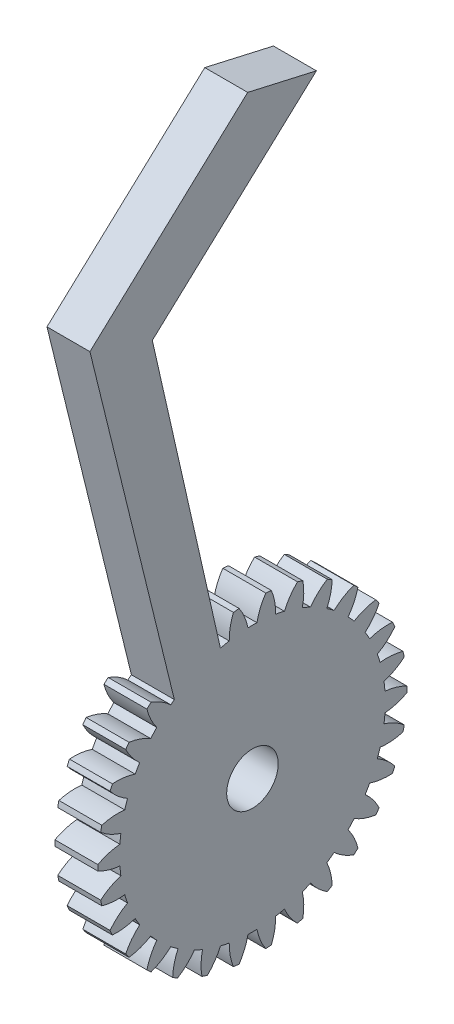
SolidWorks part; units mm, degrees
ref_plane "Plane1" through (0, 0, 0) normal (0, 0, 1) x (1, 0, 0)
ref_plane "Plane2" through (0, 0, 0) normal (0, 1, 0) x (1, 0, 0)
ref_plane "Plane3" through (0, 0, 0) normal (1, 0, 0) x (0, 0, -1)
sketch "HoldingSke" plane through (0, 0, 0) normal (0, 1, 0) x (1, 0, 0)
  line L0 (0, 0) -> (0.7698, -0.4444)
  line L1 (-15, 0) -> (100, 0) construction
  line L2 (0, 0) -> (-2.1039, 2.3779)
  line L3 (0, 0) -> (-11.863, 4.5341)
  line L4 (0, 0) -> (7.479, 4.318)
  line L5 (0, 0) -> (-46.8476, -17.4728)
  line L6 (0, 0) -> (-4.1448, -2.7965)
  line L7 (-2.1039, 2.3779) -> (8.6586, 51.2059)
  line L8 (-76.2, 54.61) -> (-75.2, 54.61)
  line L9 (-71.009, 38.7566) -> (-53.1078, 45.2721)
  line L10 (-76.2, 71.12) -> (104.1128, 71.12)
  line L11 (0, 0) -> (-5, 0)
  line L12 (-76.2, 101.6) -> (-76.158, 101.6)
  line L13 (24.9733, 27.94) -> (52.9518, 28.4284)
  line L14 (24.9733, 27.94) -> (24.9743, 27.94)
  line L15 (24.9733, 27.94) -> (100.4006, 29.5858)
  line L16 (-63.627, -1.125) -> (-12.827, -1.125)
  circle A0 centre (0, 0) radius 3
  circle A1 centre (0, 0) radius 15.4678
  circle A2 centre (0, 0) radius 37.5
  circle A3 centre (0, 0) radius 3
  dimension "MHD" = 30.9355
  dimension "Hub_dia" = 75
  dimension "Bore" = 6
  dimension "MBD" = 6
  dimension "Num_teeth" = 30
  dimension "Pitch_radius" = 180.3128
  dimension "Pitch" = 0.8889
  dimension "Width" = 5
  dimension "Overall_len" = 50
  dimension "Show_teeth" = 30
  dimension "Thickness" = 5
  dimension "OAL" = 50.0001
  dimension "T_dim" = 1
  dimension "Ap" = 20
  dimension "H" = 19.05
  dimension "Backlash" = 0.042
  dimension "Addendum_fac" = 1
  dimension "Dedendum_fac" = 1.25
  dimension "Clearance_fac" = 0.25
  dimension "Dedendum_add" = 0.001
  dimension "Module" = 1.125
sketch "BasProSke" plane through (0, 0, 0) normal (0, 1, 0) x (1, 0, 0)
  line L0 (-10, 0) -> (60, 0) construction
  line L1 (0, 0) -> (0, 18)
  line L2 (0, 0) -> (5, 0)
  line L3 (5, 0) -> (5, 18)
  line L4 (5, 18) -> (0, 18)
  dimension "Diameter" = 36
  dimension "Thickness" = 5
revolve "Base-Revolve" add sketch "BasProSke" angle 360 about L0
sketch "TooCutSke" plane through (0, 0, 0) normal (1, 0, 0) x (0, 0, -1)
  line L1 (0, 0) -> (0, 107) construction
  line L2 (0, 0) -> (-0.9567, 16.8479) construction
  line L3 (0, 0) -> (-3.5238, 33.5265) construction
  line L4 (-0.9567, 16.8479) -> (-1.7619, 16.7632) construction
  arc A0 (0.5235, 15.4589) -> (-0.5235, 15.4589) centre (0, 0) ccw
  arc A1 (1.5687, 17.957) -> (-1.5687, 17.957) centre (0, 0) ccw
  circle A2 centre (0, 0) radius 16.875 construction
  circle A3 centre (0, 0) radius 15.8573 construction
  arc A4 (-0.5235, 15.4589) -> (-1.5687, 17.957) centre (-7.1465, 14.1556) ccw
  arc A5 (1.5687, 17.957) -> (0.5235, 15.4589) centre (7.1465, 14.1556) ccw
  dimension "Root_dia" = 30.9355
  dimension "Overcut_dia" = 36.0508
  dimension "Pitch_dia" = 33.75
  dimension "Base_dia" = 31.7146
  dimension "Flank_rad" = 6.75
  dimension "Half_ang" = 6
  dimension "Half_CT" = 0.8097
extrude "ToothCut" cut sketch "TooCutSke" along normal through all
fillet "Breaks" [suppressed] radius 0.0225
fillet "RootFillets" [suppressed] radius 0.2823
pattern_circular "TeethCuts" count 30 over 360 about axis through (0, 0, 0) along (1, 0, 0) of "ToothCut", "RootFillets", "Breaks"
sketch "HubNeaOneSke" plane through (0, 0, 0) normal (-1, 0, 0) x (0, 0, 1)
  circle A0 centre (0, 0) radius 15.4678
  dimension "Diameter" = 30.9355
extrude "HubNearOne" [suppressed] add sketch "HubNeaOneSke" along normal blind 45.0001
sketch "HubNeaBotSke" plane through (0, 0, 0) normal (-1, 0, 0) x (0, 0, 1)
  circle A0 centre (0, 0) radius 15.4678
  dimension "Diameter" = 30.9355
extrude "HubNearBoth" [suppressed] add sketch "HubNeaBotSke" along normal blind 22.5
ref_plane "FarPln" through (5, 0, 0) normal (1, 0, 0) x (0, 0, -1)
sketch "HubFarSke" plane through (5, 0, 0) normal (1, 0, 0) x (0, 0, -1)
  circle A0 centre (0, 0) radius 15.4678
  dimension "Diameter" = 30.9355
extrude "HubFar" [suppressed] add sketch "HubFarSke" along normal blind 22.5
sketch "BorSke" plane through (0, 0, 0) normal (1, 0, 0) x (0, 0, -1)
  circle A0 centre (0, 0) radius 3
  dimension "Diameter" = 6
extrude "Bore" cut sketch "BorSke" along normal mid plane 100.0001
sketch "KeySke" plane through (0, 0, 0) normal (1, 0, 0) x (0, 0, -1)
  line L0 (-1, 0) -> (-1, 4)
  line L1 (-1, 4) -> (1, 4)
  line L2 (1, 4) -> (1, 0)
  line L3 (0, 0) -> (0, 34) construction
  line L4 (-1, 0) -> (1, 0)
  dimension "Offset" = 4
  dimension "Width" = 2
extrude "Keyway" [suppressed] cut sketch "KeySke" along normal mid plane 100.0001
pattern_circular "Keyway2" [suppressed] count 2 every 90 about axis through (-10, 0, 0) along (1, 0, 0)
sketch "Esquisse2" plane through (5, 0, 0) normal (1, 0, 0) x (0, 0, -1)
  line L0 (-3.7262, 15.0122) -> (-11.6565, 50.0122)
  line L1 (-11.6565, 50.0122) -> (7.45, 67.6457)
  line L2 (7.45, 67.6457) -> (-0.55, 69.4689)
  line L3 (-0.55, 69.4689) -> (-18.9217, 52.5137)
  line L4 (-18.9217, 52.5137) -> (-9.0917, 12.5137)
  line L5 (-3.7262, 15.0122) -> (-9.0917, 12.5137)
  circle A0 centre (23.3529, 39.6852) radius 27.5
  arc A1 (-8.663, 12.8142) -> (-9.51, 12.1988) centre (0, 0) ccw construction
  dimension "D1" = 55
  dimension "D2" = 40
  dimension "D3" = 35
  dimension "D4" = 25
  dimension "D5" = 26
  dimension "D6" = 8
extrude "Boss.-Extru.1" add sketch "Esquisse2" against normal blind 5 contours L2 L3 L4 L5 L0 L1
equation "' \"Module@HoldingSke\" = 6.35"
equation "' \"Num_teeth@HoldingSke\" = 12"
equation "' \"Ap@HoldingSke\" =  20"
equation "' \"Width@HoldingSke\" = 0.5 * 25.4"
equation "' \"Hub_dia@HoldingSke\"= 1 * 25.4"
equation "' \"Overall_len@HoldingSke\" = 1.0 * 25.4"
equation "' \"Bore@HoldingSke\" = 0.75 * 25.4"
equation "' \"T_dim@HoldingSke\" = 0.1 * 25.4"
equation "' \"Width@KeySke\" = 0.25 * 25.4"
equation "' \"Show_teeth@HoldingSke\" = 13"
equation "' \"Backlash@HoldingSke\" = 0.009 * 25.4"
equation "' \"Addendum_fac@HoldingSke\" = 1.0"
equation "' \"Dedendum_fac@HoldingSke\" = 1.25"
equation "' \"Dedendum_add@HoldingSke\" = 0.00005 * 25.4"
equation "' \"Clearance_fac@HoldingSke\" = 0.25"
equation "\"Pitch@HoldingSke\" = 1 / \"Module@HoldingSke\""
equation "\"Overcut_dia@TooCutSke\" = (\"Num_teeth@HoldingSke\" + 2 * \"Addendum_fac@HoldingSke\") / \"Pitch@HoldingSke\" + 0.002 * 25.4"
equation "\"Pitch_dia@TooCutSke\" = \"Num_teeth@HoldingSke\" / \"Pitch@HoldingSke\""
equation "\"Base_dia@TooCutSke\" = \"Num_teeth@HoldingSke\" / \"Pitch@HoldingSke\" * cos((\"Ap@HoldingSke\"  * 3.14159265 / 180))"
equation "\"Root_dia@TooCutSke\" = (\"Num_teeth@HoldingSke\" + 2) / \"Pitch@HoldingSke\" - 2 * (\"Addendum_fac@HoldingSke\" + \"Dedendum_fac@HoldingSke\") / \"Pitch@HoldingSke\" - \"Dedendum_add@HoldingSke\" * 2"
equation "\"Half_ang@TooCutSke\" = 180 / \"Num_teeth@HoldingSke\""
equation "\"Half_CT@TooCutSke\" = \"Num_teeth@HoldingSke\" / \"Pitch@HoldingSke\" * sin((3.14159265 / 2 / \"Num_teeth@HoldingSke\")) / 2 - 7 * \"Backlash@HoldingSke\" / 4"
equation "\"Flank_rad@TooCutSke\" = \"Num_teeth@HoldingSke\" / \"Pitch@HoldingSke\" / 5"
equation "\"Radius@RootFillets\" = \"Clearance_fac@HoldingSke\" / \"Pitch@HoldingSke\" + \"Dedendum_add@HoldingSke\""
equation "\"Break_rad@Breaks\" = 0.02 / \"Pitch@HoldingSke\""
equation "\"Thickness@HoldingSke\" = \"Width@HoldingSke\""
equation "\"OAL@HoldingSke\" = \"Thickness@HoldingSke\""
equation "\"MHD@HoldingSke\" = (\"Num_teeth@HoldingSke\" + 2) / \"Pitch@HoldingSke\" - 2 * (\"Addendum_fac@HoldingSke\" + \"Dedendum_fac@HoldingSke\")  / \"Pitch@HoldingSke\" - \"Dedendum_add@HoldingSke\" * 2"
equation "\"MBD@HoldingSke\" = (\"Num_teeth@HoldingSke\" + 2) / \"Pitch@HoldingSke\" - 2 * (\"Addendum_fac@HoldingSke\" + \"Dedendum_fac@HoldingSke\")  / \"Pitch@HoldingSke\" - \"Dedendum_add@HoldingSke\" * 2 - 0.002 * 25.4"
equation "\"MHD@HoldingSke\" = ((sgn( \"MHD@HoldingSke\" - \"Hub_dia@HoldingSke\" )-1)*( \"MHD@HoldingSke\" - \"Hub_dia@HoldingSke\" ))/-2+ \"Hub_dia@HoldingSke\""
equation "\"MBD@HoldingSke\" = ((sgn( \"MBD@HoldingSke\" - \"Bore@HoldingSke\" )-1)*( \"MBD@HoldingSke\" - \"Bore@HoldingSke\" ))/-2+ \"Bore@HoldingSke\""
equation "\"OAL@HoldingSke\" = ((sgn( \"OAL@HoldingSke\" - \"Overall_len@HoldingSke\" )+1)*( \"OAL@HoldingSke\" - \"Overall_len@HoldingSke\" ))/2 + \"Overall_len@HoldingSke\" + 0.000002 * 25.4"
equation "\"Num_teeth@TeethCuts\" = int( \"Show_teeth@HoldingSke\" ) + 1"
equation "\"Num_teeth@TeethCuts\" = ((sgn( \"Num_teeth@TeethCuts\" - \"Num_teeth@HoldingSke\" )-1)*( \"Num_teeth@TeethCuts\" - \"Num_teeth@HoldingSke\" ))/-2+ \"Num_teeth@HoldingSke\""
equation "\"Num_teeth@TeethCuts\" = ((sgn( \"Num_teeth@TeethCuts\" - 2.0)+1)*( \"Num_teeth@TeethCuts\" - 2.0))/2 +2.0"
equation "\"Angle@TeethCuts\" = 360.0 / \"Num_teeth@HoldingSke\""
equation "\"Diameter@BasProSke\" = (\"Num_teeth@HoldingSke\" + 2 * \"Addendum_fac@HoldingSke\") / \"Pitch@HoldingSke\""
equation "\"Thickness@BasProSke\"  = \"Thickness@HoldingSke\""
equation "' \"Fillet_rad@BasProSke\" =  \"Thickness@HoldingSke\" * 0.05"
equation "\"MHD@HoldingSke\" = ((sgn( \"MHD@HoldingSke\" - \"Root_dia@TooCutSke\" )-1)*( \"MHD@HoldingSke\" - \"Root_dia@TooCutSke\" ))/-2+ \"Root_dia@TooCutSke\""
equation "\"Diameter@HubNeaOneSke\" = \"MHD@HoldingSke\""
equation "\"Length@HubNearOne\" = \"OAL@HoldingSke\" - \"Thickness@BasProSke\""
equation "\"Diameter@HubNeaBotSke\" = \"MHD@HoldingSke\""
equation "\"Length@HubNearBoth\" = ( \"OAL@HoldingSke\" - \"Thickness@BasProSke\" ) / 2.0"
equation "\"Thickness@FarPln\" = \"Thickness@BasProSke\""
equation "\"Diameter@HubFarSke\" = \"MHD@HoldingSke\""
equation "\"Length@HubFar\" = ( \"OAL@HoldingSke\" - \"Thickness@BasProSke\" ) / 2.0"
equation "\"Diameter@BorSke\" = \"MBD@HoldingSke\""
equation "\"D1@Bore\" = \"OAL@HoldingSke\" * 2.0"
equation "\"D1@Keyway\" = \"OAL@HoldingSke\" * 2.0"
equation "\"Offset@KeySke\" = \"T_dim@HoldingSke\" + \"MBD@HoldingSke\" / 2.0"
